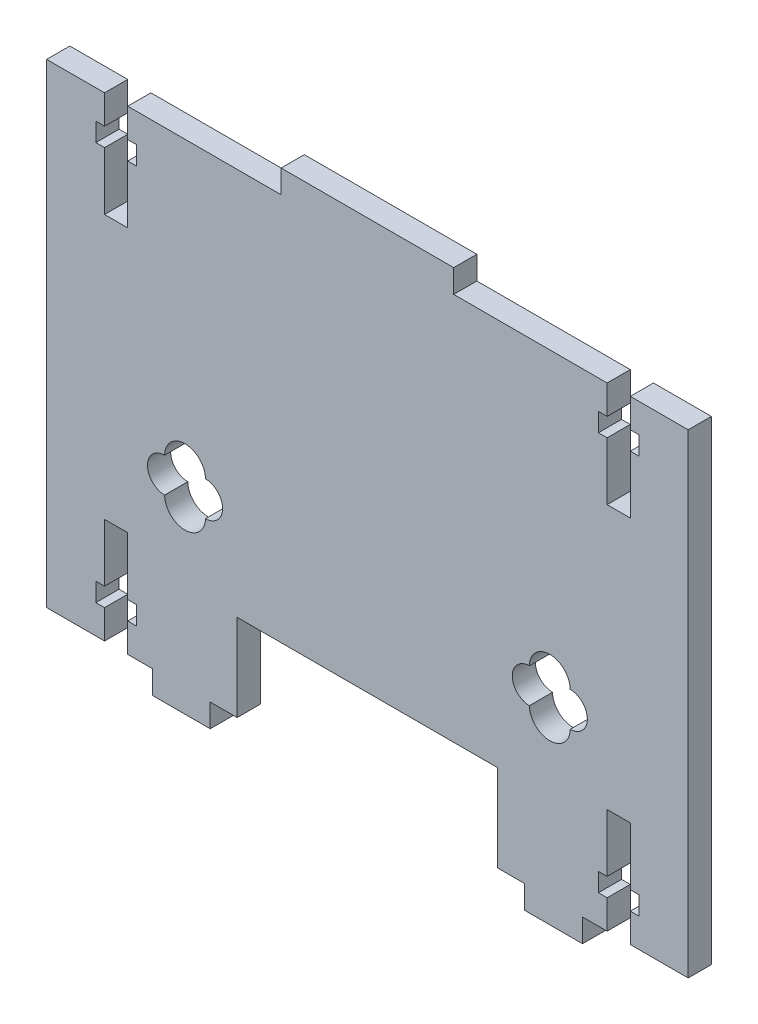
SolidWorks part; units mm, degrees
ref_plane "Front Plane" through (0, 0, 0) normal (0, 0, 1) x (1, 0, 0)
ref_plane "Top Plane" through (0, 0, 0) normal (0, 1, 0) x (1, 0, 0)
ref_plane "Right Plane" through (0, 0, 0) normal (1, 0, 0) x (0, 0, -1)
sketch "Sketch1" plane through (0, 0, 0) normal (0, 0, 1) x (1, 0, 0)
  line L1 (-55.4, 41) -> (55.4, 41)
  line L2 (-55.4, 41) -> (-55.4, -41)
  line L3 (-55.4, -41) -> (55.4, -41)
  line L4 (55.4, 41) -> (55.4, -41)
  dimension "D1" = 110.8
  dimension "D2" = 55.4
  dimension "D3" = 82
  dimension "D4" = 41
extrude "Boss-Extrude1" add sketch "Sketch1" along normal blind 4
sketch "Sketch2" plane through (0, 0, 4) normal (0, 0, 1) x (1, 0, 0)
  line L0 (43.4, -20.8) -> (43.4, -35.6452) construction
  line L13 (41.4, -32.8) -> (41.4, -22.8)
  line L14 (-55.4, 41) -> (-55.4, -41) construction
  line L15 (0, 0) -> (-49.1489, 0) construction
  line L16 (0, 0) -> (0, 26.0159) construction
  line L17 (45.4, -36) -> (45.4, -41)
  line L30 (0, 0) -> (0, 10.9555) construction
  line L43 (39.9, -36) -> (41.4, -36)
  line L80 (-43.4, 20.8) -> (-43.4, 35.6452) construction
  line L81 (-41.4, 32.8) -> (-41.4, 22.8)
  line L82 (-45.4, 36) -> (-45.4, 41)
  line L83 (-39.9, 36) -> (-41.4, 36)
  line L84 (-39.9, 32.8) -> (-39.9, 36)
  line L85 (-41.4, 32.8) -> (-39.9, 32.8)
  line L86 (-46.9, 36) -> (-45.4, 36)
  line L87 (-46.9, 32.8) -> (-46.9, 36)
  line L88 (-45.4, 32.8) -> (-46.9, 32.8)
  line L89 (-45.4, 22.8) -> (-41.4, 22.8)
  line L90 (-41.4, 41) -> (-41.4, 36)
  line L91 (-45.4, 41) -> (-41.4, 41)
  line L92 (-45.4, 22.8) -> (-45.4, 32.8)
  line L93 (55.4, 41) -> (-55.4, 41) construction
  line L94 (43.4, 20.8) -> (43.4, 35.6452) construction
  line L95 (45.4, 22.8) -> (45.4, 32.8)
  line L96 (45.4, 41) -> (41.4, 41)
  line L97 (41.4, 41) -> (41.4, 36)
  line L98 (45.4, 22.8) -> (41.4, 22.8)
  line L99 (45.4, 32.8) -> (46.9, 32.8)
  line L100 (46.9, 32.8) -> (46.9, 36)
  line L101 (46.9, 36) -> (45.4, 36)
  line L102 (41.4, 32.8) -> (39.9, 32.8)
  line L103 (39.9, 32.8) -> (39.9, 36)
  line L104 (39.9, 36) -> (41.4, 36)
  line L105 (45.4, 36) -> (45.4, 41)
  line L106 (41.4, 32.8) -> (41.4, 22.8)
  line L107 (39.9, -32.8) -> (39.9, -36)
  line L108 (41.4, -32.8) -> (39.9, -32.8)
  line L109 (46.9, -36) -> (45.4, -36)
  line L110 (46.9, -32.8) -> (46.9, -36)
  line L111 (45.4, -32.8) -> (46.9, -32.8)
  line L112 (45.4, -22.8) -> (41.4, -22.8)
  line L113 (41.4, -41) -> (41.4, -36)
  line L114 (45.4, -41) -> (41.4, -41)
  line L115 (45.4, -22.8) -> (45.4, -32.8)
  line L116 (-43.4, -20.8) -> (-43.4, -35.6452) construction
  line L117 (-45.4, -22.8) -> (-45.4, -32.8)
  line L118 (-45.4, -41) -> (-41.4, -41)
  line L119 (-41.4, -41) -> (-41.4, -36)
  line L120 (-45.4, -22.8) -> (-41.4, -22.8)
  line L121 (-45.4, -32.8) -> (-46.9, -32.8)
  line L122 (-46.9, -32.8) -> (-46.9, -36)
  line L123 (-46.9, -36) -> (-45.4, -36)
  line L124 (-41.4, -32.8) -> (-39.9, -32.8)
  line L125 (-39.9, -32.8) -> (-39.9, -36)
  line L126 (-39.9, -36) -> (-41.4, -36)
  line L127 (-45.4, -36) -> (-45.4, -41)
  line L128 (-41.4, -32.8) -> (-41.4, -22.8)
  dimension "D10" = 5
  dimension "D11" = 3.2
  dimension "D12" = 10
  dimension "D13" = 2
  dimension "D14" = 4
  dimension "D15" = 1.5
  dimension "D16" = 1.5
  dimension "D17" = 10
extrude "Cut-Extrude1" cut sketch "Sketch2" against normal blind 10
sketch "Sketch3" plane through (0, 0, 4) normal (0, 0, 1) x (1, 0, 0)
  line L4 (-22.5, -41) -> (22.5, -41)
  line L5 (22.5, -41) -> (22.5, -26)
  line L6 (-22.5, -41) -> (-22.5, -26)
  line L7 (22.5, -26) -> (-22.5, -26)
  line L8 (0, 0) -> (0, -50.9361) construction
  line L10 (-41.4, -41) -> (41.4, -41) construction
  dimension "D1" = 15
  dimension "D2" = 45
  dimension "D3" = 22.5
extrude "Cut-Extrude2" cut sketch "Sketch3" against normal blind 10
sketch "Sketch6" plane through (0, 0, 4) normal (0, 0, 1) x (1, 0, 0)
  line L0 (0, 0) -> (0, -22.9488) construction
  arc A4 (-35.0302, -13.9841) -> (-27.9698, -13.9841) centre (-31.5, -13.933) ccw
  arc A5 (-35.0302, -8.0159) -> (-35.0302, -13.9841) centre (-35, -11) ccw
  arc A6 (-27.9698, -8.0159) -> (-35.0302, -8.0159) centre (-31.5, -8.067) ccw
  arc A7 (-27.9698, -13.9841) -> (-27.9698, -8.0159) centre (-28, -11) ccw
  arc A8 (27.9698, -13.9841) -> (27.9698, -8.0159) centre (28, -11) cw
  arc A9 (27.9698, -8.0159) -> (35.0302, -8.0159) centre (31.5, -8.067) cw
  arc A10 (35.0302, -8.0159) -> (35.0302, -13.9841) centre (35, -11) cw
  arc A11 (35.0302, -13.9841) -> (27.9698, -13.9841) centre (31.5, -13.933) cw
extrude "Cut-Extrude3" cut sketch "Sketch6" against normal blind 10
sketch "Sketch8" plane through (0, 0, 4) normal (0, 0, 1) x (1, 0, 0)
  line L7 (0, 0) -> (0, 49.1972) construction
  line L8 (41.4, 41) -> (-41.4, 41) construction
  line L9 (-14.9, 41) -> (14.9, 41)
  line L10 (-14.9, 41) -> (-14.9, 45)
  line L11 (-14.9, 45) -> (14.9, 45)
  line L12 (14.9, 41) -> (14.9, 45)
  dimension "D1" = 14.9
  dimension "D2" = 14.9
  dimension "D3" = 4
extrude "Boss-Extrude2" add sketch "Sketch8" against normal blind 4
sketch "Sketch9" plane through (0, 0, 4) normal (0, 0, 1) x (1, 0, 0)
  line L0 (-41.4, -41) -> (-22.5, -41) construction
  line L1 (-37.15, -41) -> (-27.15, -41)
  line L2 (-37.15, -41) -> (-37.15, -45)
  line L3 (-37.15, -45) -> (-27.15, -45)
  line L4 (-27.15, -41) -> (-27.15, -45)
  line L10 (-41.4, -41) -> (-41.4, -36) construction
  line L11 (0, 0) -> (0, -42.612) construction
  line L12 (27.15, -41) -> (27.15, -45)
  line L13 (37.15, -45) -> (27.15, -45)
  line L14 (37.15, -41) -> (37.15, -45)
  line L15 (37.15, -41) -> (27.15, -41)
  point P12 (-32.15, -45)
  dimension "D1" = 4
  dimension "D2" = 10
  dimension "D3" = 4.25
extrude "Boss-Extrude3" add sketch "Sketch9" against normal blind 4
